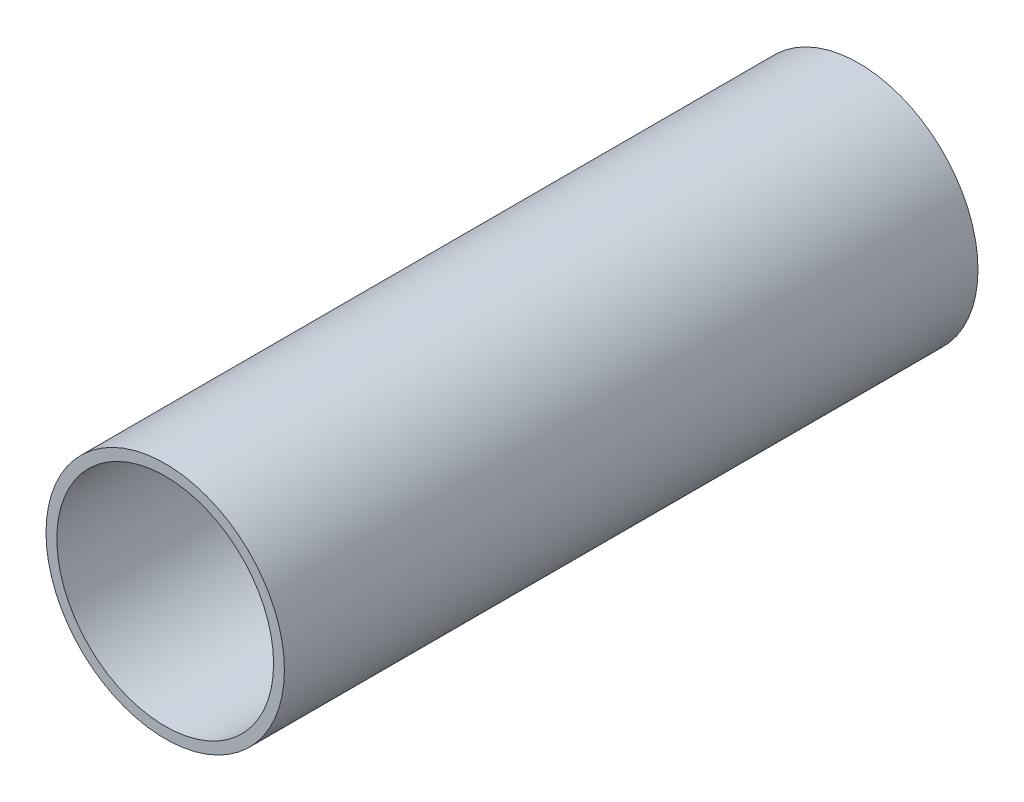
SolidWorks part; units mm, degrees
material "AISI 321 Annealed Stainless Steel (SS)"
ref_plane "Front Plane" through (0, 0, 0) normal (0, 0, 1) x (1, 0, 0)
ref_plane "Top Plane" through (0, 0, 0) normal (0, 1, 0) x (1, 0, 0)
ref_plane "Right Plane" through (0, 0, 0) normal (1, 0, 0) x (0, 0, -1)
sketch "Sketch1" plane through (0, 0, 0) normal (0, 0, 1) x (1, 0, 0)
  circle A0 centre (0, 0) radius 17.4625
  circle A1 centre (0, 0) radius 15.875
  dimension "D1" = 34.925
  dimension "D2" = 31.75
extrude "Boss-Extrude1" add sketch "Sketch1" along normal blind 101.6
